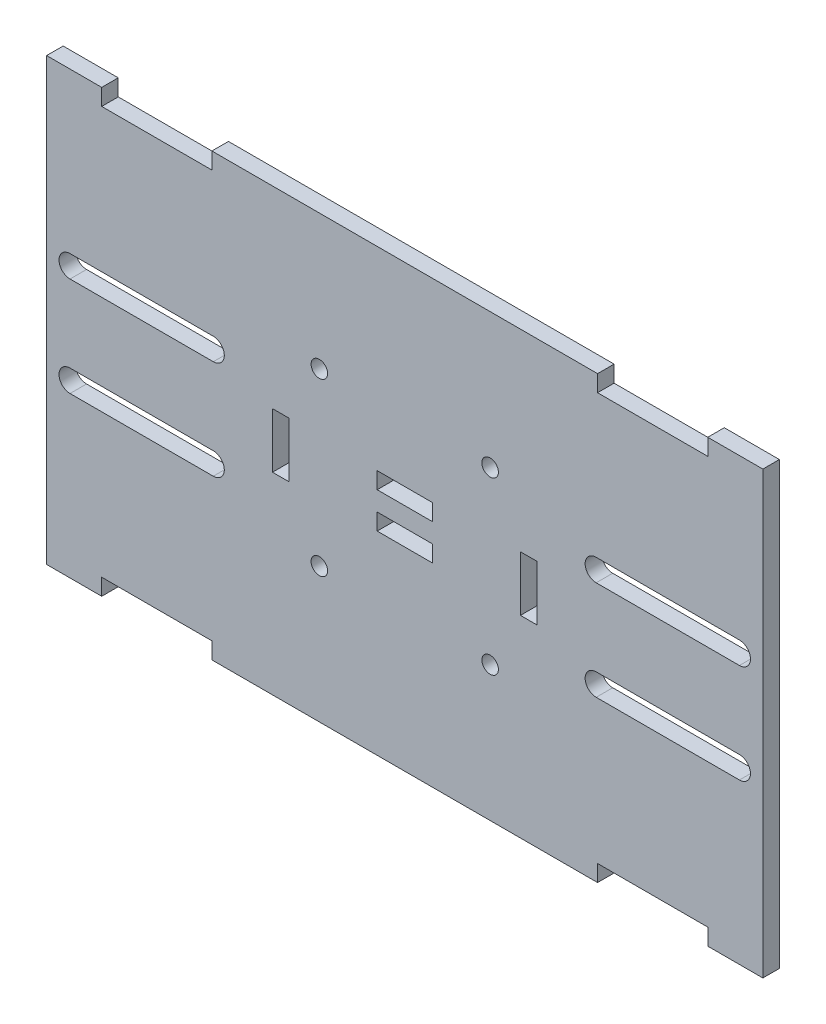
SolidWorks part; units mm, degrees
ref_plane "Front Plane" through (0, 0, 0) normal (0, 0, 1) x (1, 0, 0)
ref_plane "Top Plane" through (0, 0, 0) normal (0, 1, 0) x (1, 0, 0)
ref_plane "Right Plane" through (0, 0, 0) normal (1, 0, 0) x (0, 0, -1)
sketch "Sketch1" plane through (0, 0, 0) normal (0, 0, 1) x (1, 0, 0)
  line L0 (-55, 40) -> (-55, 37)
  line L1 (65, -40) -> (55, -40)
  line L2 (65, -40) -> (65, 40)
  line L3 (65, 40) -> (55, 40)
  line L4 (-65, -40) -> (-65, 40)
  line L5 (65, -40) -> (-65, 40) construction
  line L6 (65, 40) -> (-65, -40) construction
  line L7 (-55, 37) -> (-35, 37)
  line L8 (-35, 37) -> (-35, 40)
  line L9 (35, 40) -> (35, 37)
  line L10 (35, 37) -> (55, 37)
  line L11 (55, 37) -> (55, 40)
  line L12 (-55, -40) -> (-55, -37)
  line L13 (-55, -37) -> (-35, -37)
  line L14 (-35, -37) -> (-35, -40)
  line L15 (35, -40) -> (35, -37)
  line L16 (35, -37) -> (55, -37)
  line L17 (55, -37) -> (55, -40)
  line L18 (-55, 40) -> (-65, 40)
  line L19 (35, 40) -> (-35, 40)
  line L20 (35, -40) -> (-35, -40)
  line L21 (-55, -40) -> (-65, -40)
  line L22 (0, -40) -> (0, 40) construction
  line L23 (-65, 0) -> (65, 0) construction
  line L24 (21, -5) -> (24, -5)
  line L29 (-21, -5) -> (-24, -5)
  line L30 (-21, -5) -> (-21, 5)
  line L31 (-21, 5) -> (-24, 5)
  line L32 (-24, -5) -> (-24, 5)
  line L33 (-21, -5) -> (-24, 5) construction
  line L34 (-21, 5) -> (-24, -5) construction
  line L35 (24, -5) -> (24, 5)
  line L36 (21, 5) -> (24, 5)
  line L37 (21, -5) -> (21, 5)
  line L38 (-60.75, 11) -> (-34.75, 11)
  line L43 (15.5, -15.5) -> (-15.5, 15.5) construction
  line L44 (15.5, 15.5) -> (-15.5, -15.5) construction
  line L45 (-34.75, 7) -> (-60.75, 7)
  line L46 (-34.75, -7) -> (-60.75, -7)
  line L47 (-34.75, -11) -> (-60.75, -11)
  line L48 (34.75, 11) -> (60.75, 11)
  line L49 (60.75, 7) -> (34.75, 7)
  line L50 (34.75, -7) -> (60.75, -7)
  line L51 (60.75, -11) -> (34.75, -11)
  arc A0 (-60.75, 11) -> (-60.75, 7) centre (-60.75, 9) ccw
  arc A1 (-60.75, -11) -> (-60.75, -7) centre (-60.75, -9) cw
  arc A2 (-34.75, 7) -> (-34.75, 11) centre (-34.75, 9) ccw
  arc A3 (-34.75, -7) -> (-34.75, -11) centre (-34.75, -9) cw
  arc A4 (34.75, -7) -> (34.75, -11) centre (34.75, -9) ccw
  arc A5 (60.75, -11) -> (60.75, -7) centre (60.75, -9) ccw
  arc A6 (60.75, 11) -> (60.75, 7) centre (60.75, 9) cw
  arc A7 (34.75, 7) -> (34.75, 11) centre (34.75, 9) cw
  circle A8 centre (15.5, 15.5) radius 1.5
  circle A9 centre (-15.5, 15.5) radius 1.5
  circle A10 centre (15.5, -15.5) radius 1.5
  circle A11 centre (-15.5, -15.5) radius 1.5
  point P0 (0, 0)
  point P23 (36.5719, 15)
  point P26 (0, 25.5)
  point P27 (-22.5, 0)
  point P32 (0, 0)
  dimension "D13" = 4
  dimension "D16" = 4
  dimension "D19" = 3
  dimension "D1" = 130
  dimension "D2" = 10
  dimension "D3" = 3
  dimension "D4" = 20
  dimension "D5" = 10
  dimension "D6" = 80
  dimension "D7" = 10
  dimension "D8" = 10
  dimension "D9" = 20
  dimension "D10" = 3
  dimension "D11" = 10
  dimension "D12" = 18
  dimension "D14" = 60.75
  dimension "D15" = 26
  dimension "D17" = 31
  dimension "D18" = 31
extrude "Boss-Extrude1" add sketch "Sketch1" along normal blind 3
sketch "Sketch2" plane through (0, 0, 3) normal (0, 0, 1) x (1, 0, 0)
  line L0 (65, -40) -> (65, 40) construction
  line L7 (5, -1.75) -> (-5, -4.75) construction
  line L8 (5, 4.75) -> (-5, 4.75)
  line L9 (5, 4.75) -> (5, 1.75)
  line L10 (5, 1.75) -> (-5, 1.75)
  line L11 (-5, 4.75) -> (-5, 1.75)
  line L12 (5, 4.75) -> (-5, 1.75) construction
  line L13 (5, 1.75) -> (-5, 4.75) construction
  line L14 (5, -4.75) -> (-5, -1.75) construction
  line L15 (-5, -4.75) -> (-5, -1.75)
  line L16 (5, -1.75) -> (-5, -1.75)
  line L17 (5, -4.75) -> (5, -1.75)
  line L18 (5, -4.75) -> (-5, -4.75)
  point P12 (0, 3.25)
  point P22 (5, -3.25)
  dimension "D1" = 10
  dimension "D2" = 3
  dimension "D3" = 60
extrude "Cut-Extrude2" cut sketch "Sketch2" against normal up to surface (3 mm away) up to face at (17, -15.5, 0)
